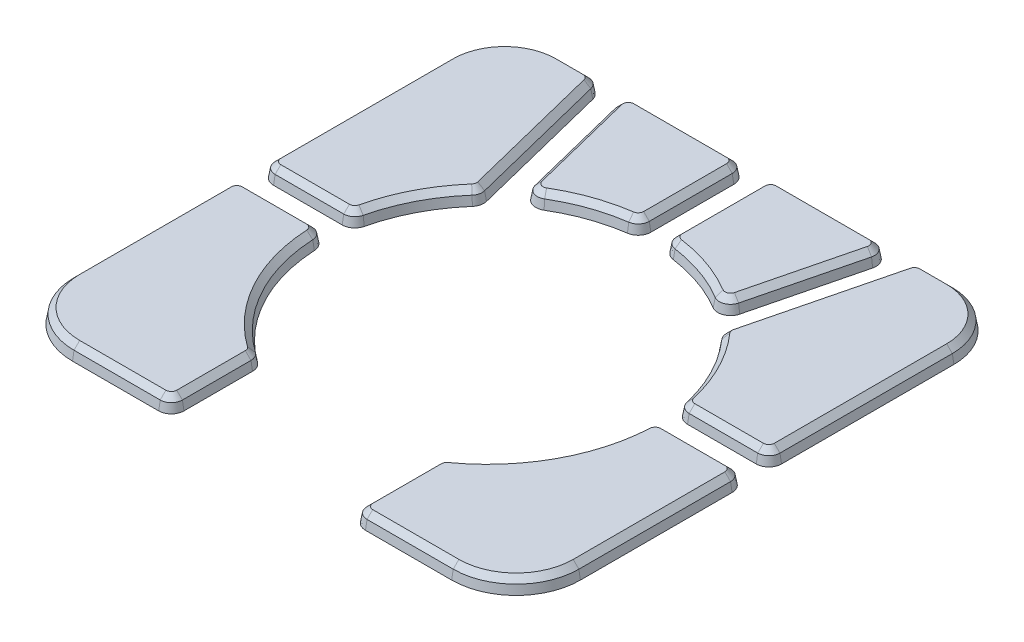
SolidWorks part; units mm, degrees
ref_plane "Front Plane" through (0, 0, 0) normal (0, 0, 1) x (1, 0, 0)
ref_plane "Top Plane" through (0, 0, 0) normal (0, 1, 0) x (1, 0, 0)
ref_plane "Right Plane" through (0, 0, 0) normal (1, 0, 0) x (0, 0, -1)
sketch "Sketch1" plane through (0, 0, 0) normal (0, 1, 0) x (1, 0, 0)
  line B0 (-29.3235, 46.4) -> (-34, 46.4)
  line B1 (-43.4, 37) -> (-43.4, 7)
  line B2 (-42, 5.6) -> (-30.0545, 5.6)
  line B3 (-21.8237, 20.707) -> (-27.965, 45.3387)
  line B4 (-4.3, 46.4) -> (-20.4602, 46.4)
  line B5 (-21.8186, 44.6613) -> (-17.2014, 26.1429)
  line B6 (-2.9, 30.5579) -> (-2.9, 45)
  line B7 (20.4602, 46.4) -> (4.3, 46.4)
  line B8 (2.9, 45) -> (2.9, 30.5579)
  line B9 (17.2014, 26.1429) -> (21.8186, 44.6613)
  line B10 (34, 46.4) -> (29.3235, 46.4)
  line B11 (27.965, 45.3387) -> (21.8237, 20.707)
  line B12 (30.0545, 5.6) -> (42, 5.6)
  line B13 (43.4, 7) -> (43.4, 37)
  line B14 (16.6, -25.0654) -> (16.6, -37)
  line B15 (18, -38.4) -> (33, -38.4)
  line B16 (43.4, -28) -> (43.4, -1.6)
  line B17 (42, -0.2) -> (30.8175, -0.2)
  line B18 (-30.8175, -0.2) -> (-42, -0.2)
  line B19 (-43.4, -1.6) -> (-43.4, -28)
  line B20 (-33, -38.4) -> (-18, -38.4)
  line B21 (-16.6, -37) -> (-16.6, -25.0654)
  arc B22 (-27.965, 45.3387) -> (-29.3235, 46.4) centre (-29.3235, 45) ccw
  arc B23 (-34, 46.4) -> (-43.4, 37) centre (-34, 37) ccw
  arc B24 (-43.4, 7) -> (-42, 5.6) centre (-42, 7) ccw
  arc B25 (-30.0545, 5.6) -> (-28.691, 6.6824) centre (-30.0545, 7) ccw
  arc B26 (-22.1304, 19.4442) -> (-28.691, 6.6824) centre (0, 0) ccw
  arc B27 (-22.1304, 19.4442) -> (-21.8237, 20.707) centre (-23.1821, 20.3683) ccw
  arc B28 (-2.9, 45) -> (-4.3, 46.4) centre (-4.3, 45) ccw
  arc B29 (-20.4602, 46.4) -> (-21.8186, 44.6613) centre (-20.4602, 45) ccw
  arc B30 (-17.2014, 26.1429) -> (-15.1243, 25.2802) centre (-15.843, 26.4816) ccw
  arc B31 (-4.1049, 29.1716) -> (-15.1243, 25.2802) centre (0, 0) ccw
  arc B32 (-4.1049, 29.1716) -> (-2.9, 30.5579) centre (-4.3, 30.5579) ccw
  arc B33 (21.8186, 44.6613) -> (20.4602, 46.4) centre (20.4602, 45) ccw
  arc B34 (4.3, 46.4) -> (2.9, 45) centre (4.3, 45) ccw
  arc B35 (2.9, 30.5579) -> (4.1049, 29.1716) centre (4.3, 30.5579) ccw
  arc B36 (15.1243, 25.2802) -> (4.1049, 29.1716) centre (0, 0) ccw
  arc B37 (15.1243, 25.2802) -> (17.2014, 26.1429) centre (15.843, 26.4816) ccw
  arc B38 (43.4, 37) -> (34, 46.4) centre (34, 37) ccw
  arc B39 (29.3235, 46.4) -> (27.965, 45.3387) centre (29.3235, 45) ccw
  arc B40 (21.8237, 20.707) -> (22.1304, 19.4442) centre (23.1821, 20.3683) ccw
  arc B41 (28.691, 6.6824) -> (22.1304, 19.4442) centre (0, 0) ccw
  arc B42 (28.691, 6.6824) -> (30.0545, 5.6) centre (30.0545, 7) ccw
  arc B43 (42, 5.6) -> (43.4, 7) centre (42, 7) ccw
  arc B44 (30.8175, -0.2) -> (29.4193, -1.5274) centre (30.8175, -1.6) ccw
  arc B45 (17.1834, -23.9283) -> (29.4193, -1.5274) centre (0, 0) ccw
  arc B46 (17.1834, -23.9283) -> (16.6, -25.0654) centre (18, -25.0654) ccw
  arc B47 (16.6, -37) -> (18, -38.4) centre (18, -37) ccw
  arc B48 (33, -38.4) -> (43.4, -28) centre (33, -28) ccw
  arc B49 (43.4, -1.6) -> (42, -0.2) centre (42, -1.6) ccw
  arc B50 (-29.4193, -1.5274) -> (-30.8175, -0.2) centre (-30.8175, -1.6) ccw
  arc B51 (-42, -0.2) -> (-43.4, -1.6) centre (-42, -1.6) ccw
  arc B52 (-43.4, -28) -> (-33, -38.4) centre (-33, -28) ccw
  arc B53 (-18, -38.4) -> (-16.6, -37) centre (-18, -37) ccw
  arc B54 (-16.6, -25.0654) -> (-17.1834, -23.9283) centre (-18, -25.0654) ccw
  arc B55 (-29.4193, -1.5274) -> (-17.1834, -23.9283) centre (0, 0) ccw
sketch_block_instance "buttonTopSurfaceNoChamfer-1"
sketch_block "buttonTopSurfaceNoChamfer"
sketch "Sketch2" plane through (0, 0, 0) normal (0, 1, 0) x (1, 0, 0)
  line L0 (-4.3, 46.4) -> (-20.4602, 46.4) construction
  line L1 (-21.8186, 44.6613) -> (-17.2014, 26.1429) construction
  line L2 (-2.9, 30.5579) -> (-2.9, 45) construction
  line L3 (-42, 5.6) -> (-30.0545, 5.6) construction
  line L4 (-43.4, 37) -> (-43.4, 7) construction
  line L5 (-29.3235, 46.4) -> (-34, 46.4) construction
  line L6 (-21.8237, 20.707) -> (-27.965, 45.3387) construction
  line L7 (20.4602, 46.4) -> (4.3, 46.4) construction
  line L8 (2.9, 45) -> (2.9, 30.5579) construction
  line L9 (17.2014, 26.1429) -> (21.8186, 44.6613) construction
  line L10 (27.965, 45.3387) -> (21.8237, 20.707) construction
  line L11 (30.0545, 5.6) -> (42, 5.6) construction
  line L12 (43.4, 7) -> (43.4, 37) construction
  line L13 (34, 46.4) -> (29.3235, 46.4) construction
  line L14 (16.6, -25.0654) -> (16.6, -37) construction
  line L15 (42, -0.2) -> (30.8175, -0.2) construction
  line L16 (43.4, -28) -> (43.4, -1.6) construction
  line L17 (18, -38.4) -> (33, -38.4) construction
  line L18 (-33, -38.4) -> (-18, -38.4) construction
  line L19 (-16.6, -37) -> (-16.6, -25.0654) construction
  line L20 (-30.8175, -0.2) -> (-42, -0.2) construction
  line L21 (-43.4, -1.6) -> (-43.4, -28) construction
  line L22 (-4.3, 46.4) -> (-20.4602, 46.4) construction
  line L23 (-21.8186, 44.6613) -> (-17.2014, 26.1429) construction
  line L24 (-2.9, 30.5579) -> (-2.9, 45) construction
  line L25 (-42, 5.6) -> (-30.0545, 5.6) construction
  line L26 (-43.4, 37) -> (-43.4, 7) construction
  line L27 (-29.3235, 46.4) -> (-34, 46.4) construction
  line L28 (-21.8237, 20.707) -> (-27.965, 45.3387) construction
  line L29 (20.4602, 46.4) -> (4.3, 46.4) construction
  line L30 (2.9, 45) -> (2.9, 30.5579) construction
  line L31 (17.2014, 26.1429) -> (21.8186, 44.6613) construction
  line L32 (27.965, 45.3387) -> (21.8237, 20.707) construction
  line L33 (30.0545, 5.6) -> (42, 5.6) construction
  line L34 (43.4, 7) -> (43.4, 37) construction
  line L35 (34, 46.4) -> (29.3235, 46.4) construction
  line L36 (16.6, -25.0654) -> (16.6, -37) construction
  line L37 (42, -0.2) -> (30.8175, -0.2) construction
  line L38 (43.4, -28) -> (43.4, -1.6) construction
  line L39 (18, -38.4) -> (33, -38.4) construction
  line L40 (-33, -38.4) -> (-18, -38.4) construction
  line L41 (-16.6, -37) -> (-16.6, -25.0654) construction
  line L42 (-30.8175, -0.2) -> (-42, -0.2) construction
  line L43 (-43.4, -1.6) -> (-43.4, -28) construction
  line L44 (-4.3, 47.2) -> (-20.4602, 47.2)
  line L45 (-22.5948, 44.4678) -> (-17.9777, 25.9494)
  line L46 (-2.1, 30.5579) -> (-2.1, 45)
  line L47 (-42, 4.8) -> (-30.0545, 4.8)
  line L48 (-21.0474, 20.9005) -> (-27.1888, 45.5322)
  line L49 (-29.3235, 47.2) -> (-34, 47.2)
  line L50 (-44.2, 37) -> (-44.2, 7)
  line L51 (20.4602, 47.2) -> (4.3, 47.2)
  line L52 (2.1, 45) -> (2.1, 30.5579)
  line L53 (17.9777, 25.9494) -> (22.5948, 44.4678)
  line L54 (27.1888, 45.5322) -> (21.0474, 20.9005)
  line L55 (30.0545, 4.8) -> (42, 4.8)
  line L56 (44.2, 7) -> (44.2, 37)
  line L57 (34, 47.2) -> (29.3235, 47.2)
  line L58 (15.8, -25.0654) -> (15.8, -37)
  line L59 (18, -39.2) -> (33, -39.2)
  line L60 (44.2, -28) -> (44.2, -1.6)
  line L61 (42, 0.6) -> (30.8175, 0.6)
  line L62 (-33, -39.2) -> (-18, -39.2)
  line L63 (-15.8, -37) -> (-15.8, -25.0654)
  line L64 (-30.8175, 0.6) -> (-42, 0.6)
  line L65 (-44.2, -1.6) -> (-44.2, -28)
  arc A0 (-20.4602, 46.4) -> (-21.8186, 44.6613) centre (-20.4602, 45) ccw construction
  arc A1 (-17.2014, 26.1429) -> (-15.1243, 25.2802) centre (-15.843, 26.4816) ccw construction
  arc A2 (-4.1049, 29.1716) -> (-15.1243, 25.2802) centre (0, 0) ccw construction
  arc A3 (-4.1049, 29.1716) -> (-2.9, 30.5579) centre (-4.3, 30.5579) ccw construction
  arc A4 (-2.9, 45) -> (-4.3, 46.4) centre (-4.3, 45) ccw construction
  arc A5 (-22.1304, 19.4442) -> (-21.8237, 20.707) centre (-23.1821, 20.3683) ccw construction
  arc A6 (-22.1304, 19.4442) -> (-28.691, 6.6824) centre (0, 0) ccw construction
  arc A7 (-30.0545, 5.6) -> (-28.691, 6.6824) centre (-30.0545, 7) ccw construction
  arc A8 (-43.4, 7) -> (-42, 5.6) centre (-42, 7) ccw construction
  arc A9 (-34, 46.4) -> (-43.4, 37) centre (-34, 37) ccw construction
  arc A10 (-27.965, 45.3387) -> (-29.3235, 46.4) centre (-29.3235, 45) ccw construction
  arc A11 (4.3, 46.4) -> (2.9, 45) centre (4.3, 45) ccw construction
  arc A12 (2.9, 30.5579) -> (4.1049, 29.1716) centre (4.3, 30.5579) ccw construction
  arc A13 (15.1243, 25.2802) -> (4.1049, 29.1716) centre (0, 0) ccw construction
  arc A14 (15.1243, 25.2802) -> (17.2014, 26.1429) centre (15.843, 26.4816) ccw construction
  arc A15 (21.8186, 44.6613) -> (20.4602, 46.4) centre (20.4602, 45) ccw construction
  arc A16 (21.8237, 20.707) -> (22.1304, 19.4442) centre (23.1821, 20.3683) ccw construction
  arc A17 (28.691, 6.6824) -> (22.1304, 19.4442) centre (0, 0) ccw construction
  arc A18 (28.691, 6.6824) -> (30.0545, 5.6) centre (30.0545, 7) ccw construction
  arc A19 (42, 5.6) -> (43.4, 7) centre (42, 7) ccw construction
  arc A20 (43.4, 37) -> (34, 46.4) centre (34, 37) ccw construction
  arc A21 (29.3235, 46.4) -> (27.965, 45.3387) centre (29.3235, 45) ccw construction
  arc A22 (17.1834, -23.9283) -> (16.6, -25.0654) centre (18, -25.0654) ccw construction
  arc A23 (17.1834, -23.9283) -> (29.4193, -1.5274) centre (0, 0) ccw construction
  arc A24 (30.8175, -0.2) -> (29.4193, -1.5274) centre (30.8175, -1.6) ccw construction
  arc A25 (43.4, -1.6) -> (42, -0.2) centre (42, -1.6) ccw construction
  arc A26 (33, -38.4) -> (43.4, -28) centre (33, -28) ccw construction
  arc A27 (16.6, -37) -> (18, -38.4) centre (18, -37) ccw construction
  arc A28 (-18, -38.4) -> (-16.6, -37) centre (-18, -37) ccw construction
  arc A29 (-16.6, -25.0654) -> (-17.1834, -23.9283) centre (-18, -25.0654) ccw construction
  arc A30 (-29.4193, -1.5274) -> (-17.1834, -23.9283) centre (0, 0) ccw construction
  arc A31 (-29.4193, -1.5274) -> (-30.8175, -0.2) centre (-30.8175, -1.6) ccw construction
  arc A32 (-42, -0.2) -> (-43.4, -1.6) centre (-42, -1.6) ccw construction
  arc A33 (-43.4, -28) -> (-33, -38.4) centre (-33, -28) ccw construction
  arc A34 (-20.4602, 46.4) -> (-21.8186, 44.6613) centre (-20.4602, 45) ccw construction
  arc A35 (-17.2014, 26.1429) -> (-15.1243, 25.2802) centre (-15.843, 26.4816) ccw construction
  arc A36 (-4.1049, 29.1716) -> (-15.1243, 25.2802) centre (0, 0) ccw construction
  arc A37 (-4.1049, 29.1716) -> (-2.9, 30.5579) centre (-4.3, 30.5579) ccw construction
  arc A38 (-2.9, 45) -> (-4.3, 46.4) centre (-4.3, 45) ccw construction
  arc A39 (-22.1304, 19.4442) -> (-21.8237, 20.707) centre (-23.1821, 20.3683) ccw construction
  arc A40 (-22.1304, 19.4442) -> (-28.691, 6.6824) centre (0, 0) ccw construction
  arc A41 (-30.0545, 5.6) -> (-28.691, 6.6824) centre (-30.0545, 7) ccw construction
  arc A42 (-43.4, 7) -> (-42, 5.6) centre (-42, 7) ccw construction
  arc A43 (-34, 46.4) -> (-43.4, 37) centre (-34, 37) ccw construction
  arc A44 (-27.965, 45.3387) -> (-29.3235, 46.4) centre (-29.3235, 45) ccw construction
  arc A45 (4.3, 46.4) -> (2.9, 45) centre (4.3, 45) ccw construction
  arc A46 (2.9, 30.5579) -> (4.1049, 29.1716) centre (4.3, 30.5579) ccw construction
  arc A47 (15.1243, 25.2802) -> (4.1049, 29.1716) centre (0, 0) ccw construction
  arc A48 (15.1243, 25.2802) -> (17.2014, 26.1429) centre (15.843, 26.4816) ccw construction
  arc A49 (21.8186, 44.6613) -> (20.4602, 46.4) centre (20.4602, 45) ccw construction
  arc A50 (21.8237, 20.707) -> (22.1304, 19.4442) centre (23.1821, 20.3683) ccw construction
  arc A51 (28.691, 6.6824) -> (22.1304, 19.4442) centre (0, 0) ccw construction
  arc A52 (28.691, 6.6824) -> (30.0545, 5.6) centre (30.0545, 7) ccw construction
  arc A53 (42, 5.6) -> (43.4, 7) centre (42, 7) ccw construction
  arc A54 (43.4, 37) -> (34, 46.4) centre (34, 37) ccw construction
  arc A55 (29.3235, 46.4) -> (27.965, 45.3387) centre (29.3235, 45) ccw construction
  arc A56 (17.1834, -23.9283) -> (16.6, -25.0654) centre (18, -25.0654) ccw construction
  arc A57 (17.1834, -23.9283) -> (29.4193, -1.5274) centre (0, 0) ccw construction
  arc A58 (30.8175, -0.2) -> (29.4193, -1.5274) centre (30.8175, -1.6) ccw construction
  arc A59 (43.4, -1.6) -> (42, -0.2) centre (42, -1.6) ccw construction
  arc A60 (33, -38.4) -> (43.4, -28) centre (33, -28) ccw construction
  arc A61 (16.6, -37) -> (18, -38.4) centre (18, -37) ccw construction
  arc A62 (-18, -38.4) -> (-16.6, -37) centre (-18, -37) ccw construction
  arc A63 (-16.6, -25.0654) -> (-17.1834, -23.9283) centre (-18, -25.0654) ccw construction
  arc A64 (-29.4193, -1.5274) -> (-17.1834, -23.9283) centre (0, 0) ccw construction
  arc A65 (-29.4193, -1.5274) -> (-30.8175, -0.2) centre (-30.8175, -1.6) ccw construction
  arc A66 (-42, -0.2) -> (-43.4, -1.6) centre (-42, -1.6) ccw construction
  arc A67 (-43.4, -28) -> (-33, -38.4) centre (-33, -28) ccw construction
  arc A68 (-20.4602, 47.2) -> (-22.5948, 44.4678) centre (-20.4602, 45) ccw
  arc A69 (-17.9777, 25.9494) -> (-14.7135, 24.5937) centre (-15.843, 26.4816) ccw
  arc A70 (-3.9934, 28.3794) -> (-14.7135, 24.5937) centre (0, 0) ccw
  arc A71 (-3.9934, 28.3794) -> (-2.1, 30.5579) centre (-4.3, 30.5579) ccw
  arc A72 (-2.1, 45) -> (-4.3, 47.2) centre (-4.3, 45) ccw
  arc A73 (-30.0545, 4.8) -> (-27.9119, 6.501) centre (-30.0545, 7) ccw
  arc A74 (-21.5294, 18.9162) -> (-27.9119, 6.501) centre (0, 0) ccw
  arc A75 (-21.5294, 18.9162) -> (-21.0474, 20.9005) centre (-23.1821, 20.3683) ccw
  arc A76 (-27.1888, 45.5322) -> (-29.3235, 47.2) centre (-29.3235, 45) ccw
  arc A77 (-34, 47.2) -> (-44.2, 37) centre (-34, 37) ccw
  arc A78 (-44.2, 7) -> (-42, 4.8) centre (-42, 7) ccw
  arc A79 (4.3, 47.2) -> (2.1, 45) centre (4.3, 45) ccw
  arc A80 (2.1, 30.5579) -> (3.9934, 28.3794) centre (4.3, 30.5579) ccw
  arc A81 (14.7135, 24.5937) -> (3.9934, 28.3794) centre (0, 0) ccw
  arc A82 (14.7135, 24.5937) -> (17.9777, 25.9494) centre (15.843, 26.4816) ccw
  arc A83 (22.5948, 44.4678) -> (20.4602, 47.2) centre (20.4602, 45) ccw
  arc A84 (21.0474, 20.9005) -> (21.5294, 18.9162) centre (23.1821, 20.3683) ccw
  arc A85 (27.9119, 6.501) -> (21.5294, 18.9162) centre (0, 0) ccw
  arc A86 (27.9119, 6.501) -> (30.0545, 4.8) centre (30.0545, 7) ccw
  arc A87 (42, 4.8) -> (44.2, 7) centre (42, 7) ccw
  arc A88 (44.2, 37) -> (34, 47.2) centre (34, 37) ccw
  arc A89 (29.3235, 47.2) -> (27.1888, 45.5322) centre (29.3235, 45) ccw
  arc A90 (15.8, -37) -> (18, -39.2) centre (18, -37) ccw
  arc A91 (33, -39.2) -> (44.2, -28) centre (33, -28) ccw
  arc A92 (44.2, -1.6) -> (42, 0.6) centre (42, -1.6) ccw
  arc A93 (30.8175, 0.6) -> (28.6204, -1.4859) centre (30.8175, -1.6) ccw
  arc A94 (16.7167, -23.2785) -> (28.6204, -1.4859) centre (0, 0) ccw
  arc A95 (16.7167, -23.2785) -> (15.8, -25.0654) centre (18, -25.0654) ccw
  arc A96 (-18, -39.2) -> (-15.8, -37) centre (-18, -37) ccw
  arc A97 (-15.8, -25.0654) -> (-16.7167, -23.2785) centre (-18, -25.0654) ccw
  arc A98 (-28.6204, -1.4859) -> (-16.7167, -23.2785) centre (0, 0) ccw
  arc A99 (-28.6204, -1.4859) -> (-30.8175, 0.6) centre (-30.8175, -1.6) ccw
  arc A100 (-42, 0.6) -> (-44.2, -1.6) centre (-42, -1.6) ccw
  arc A101 (-44.2, -28) -> (-33, -39.2) centre (-33, -28) ccw
  dimension "D1" = 0.8
extrude "Boss-Extrude1" add sketch "Sketch2" along normal blind 2.5 draft 10
chamfer "Chamfer1" distance 1 angle 35 10 edges at (-43.7592, 2.5, 14.8) (-43.2439, 2.5, 0.3561) (-36.4087, 2.5, -0.1592) (-29.6062, 2.5, 0.3242) (-25.5383, 2.5, 13.9497) (-16.4348, 2.5, 24.2624) (-16.2408, 2.5, 31.0327) (-16.7561, 2.5, 38.2439) (-25.5, 2.5, 38.7592) (-40.6079, 2.5, 35.6079)
chamfer "Chamfer2" distance 1 angle 35 10 edges at (-28.2404, 2.5, -46.3863) (-31.6617, 2.5, -46.7592) (-24.5458, 2.5, -33.1097) (-40.9008, 2.5, -43.9008) (-21.4726, 2.5, -19.9531) (-43.7592, 2.5, -22) (-25.8802, 2.5, -13.3047) (-43.2439, 2.5, -5.7561) (-28.9608, 2.5, -5.6222) (-36.0273, 2.5, -5.2408)
chamfer "Chamfer3" distance 1 angle 35 8 edges at (-12.3801, 2.5, -46.7592) (-21.8464, 2.5, -46.0831) (-3.0561, 2.5, -46.2439) (-19.8585, 2.5, -35.3152) (-2.5408, 2.5, -37.779) (-16.5178, 2.5, -24.857) (-2.9722, 2.5, -29.4039) (-9.6899, 2.5, -27.4391)
chamfer "Chamfer4" distance 1 angle 35 8 edges at (12.3801, 2.5, -46.7592) (3.0561, 2.5, -46.2439) (21.8464, 2.5, -46.0831) (2.5408, 2.5, -37.779) (19.8585, 2.5, -35.3152) (2.9722, 2.5, -29.4039) (16.5178, 2.5, -24.857) (9.6899, 2.5, -27.4391)
chamfer "Chamfer5" distance 1 angle 35 10 edges at (40.9008, 2.5, -43.9008) (31.6617, 2.5, -46.7592) (43.7592, 2.5, -22) (28.2404, 2.5, -46.3863) (43.2439, 2.5, -5.7561) (24.5458, 2.5, -33.1097) (36.0273, 2.5, -5.2408) (21.4726, 2.5, -19.9531) (28.9608, 2.5, -5.6222) (25.8802, 2.5, -13.3047)
chamfer "Chamfer6" distance 1 angle 35 10 edges at (29.6062, 2.5, 0.3242) (25.5383, 2.5, 13.9497) (36.4087, 2.5, -0.1592) (16.4348, 2.5, 24.2624) (43.2439, 2.5, 0.3561) (16.2408, 2.5, 31.0327) (43.7592, 2.5, 14.8) (16.7561, 2.5, 38.2439) (40.6079, 2.5, 35.6079) (25.5, 2.5, 38.7592)
sketch "Sketch3" plane through (0, 0, 0) normal (0, -1, 0) x (1, 0, 0)
  line L0 (-24, 31) -> (24, 31) construction
  arc A1 (-16.7167, 23.2785) -> (-28.6204, 1.4859) centre (0, 0) ccw construction
  point P0 (0, 0)
  circle B0 centre (24, 31) radius 2.1
  circle B1 centre (36, 12.2) radius 2.1
  circle B2 centre (36, -13) radius 2.1
  circle B3 centre (31.4, -34.3142) radius 2.1
  circle B4 centre (13.4412, -31.7294) radius 2.1
  circle B5 centre (7.9, -41.4) radius 2.1
  circle B6 centre (-7.9, -41.4) radius 2.1
  circle B7 centre (-13.4412, -31.7294) radius 2.1
  circle B8 centre (-31.4, -34.3142) radius 2.1
  circle B9 centre (-36, -13) radius 2.1
  circle B10 centre (-24, 31) radius 2.1
  circle B11 centre (-36, 12.2) radius 2.1
sketch_block_instance "magnetHoles-1"
sketch_block "magnetHoles"
extrude "Cut-Extrude1" [suppressed] cut sketch "Sketch3" against normal blind 2
sketch "Sketch5" plane through (0, 0, 0) normal (0, -1, 0) x (-1, 0, 0)
  line L0 (36, -12.2) -> (24, -31) construction
  circle A0 centre (24, -31) radius 2.15
  circle A1 centre (36, -12.2) radius 2.25
  circle A2 centre (30, -21.6) radius 2.2
  circle A3 centre (24, -31) radius 2.1 construction
  circle A4 centre (36, -12.2) radius 2.1 construction
  dimension "D1" = 0.05
  dimension "D2" = 4.3
  dimension "D3" = 4.4
  dimension "D4" = 0.15
  dimension "D5" = 4.5
extrude "Cut-Extrude3" [suppressed] cut sketch "Sketch5" against normal blind 2
sketch "Sketch4" plane through (0, 0, 0) normal (0, -1, 0) x (1, 0, 0)
  circle A166 centre (-24, 31) radius 2.2
  circle A167 centre (-36, 12.2) radius 2.2
  circle A168 centre (-36, -13) radius 2.2
  circle A169 centre (-31.4, -34.3142) radius 2.2
  circle A170 centre (-13.4412, -31.7294) radius 2.2
  circle A171 centre (-7.9, -41.4) radius 2.2
  circle A172 centre (7.9, -41.4) radius 2.2
  circle A173 centre (13.4412, -31.7294) radius 2.2
  circle A174 centre (31.4, -34.3142) radius 2.2
  circle A175 centre (36, -13) radius 2.2
  circle A176 centre (36, 12.2) radius 2.2
  circle A177 centre (24, 31) radius 2.2
  circle A178 centre (-24, 31) radius 2.1 construction
  dimension "D1" = 0.1
  dimension "D2" = 4.4
extrude "Cut-Extrude2" cut sketch "Sketch4" against normal blind 2
